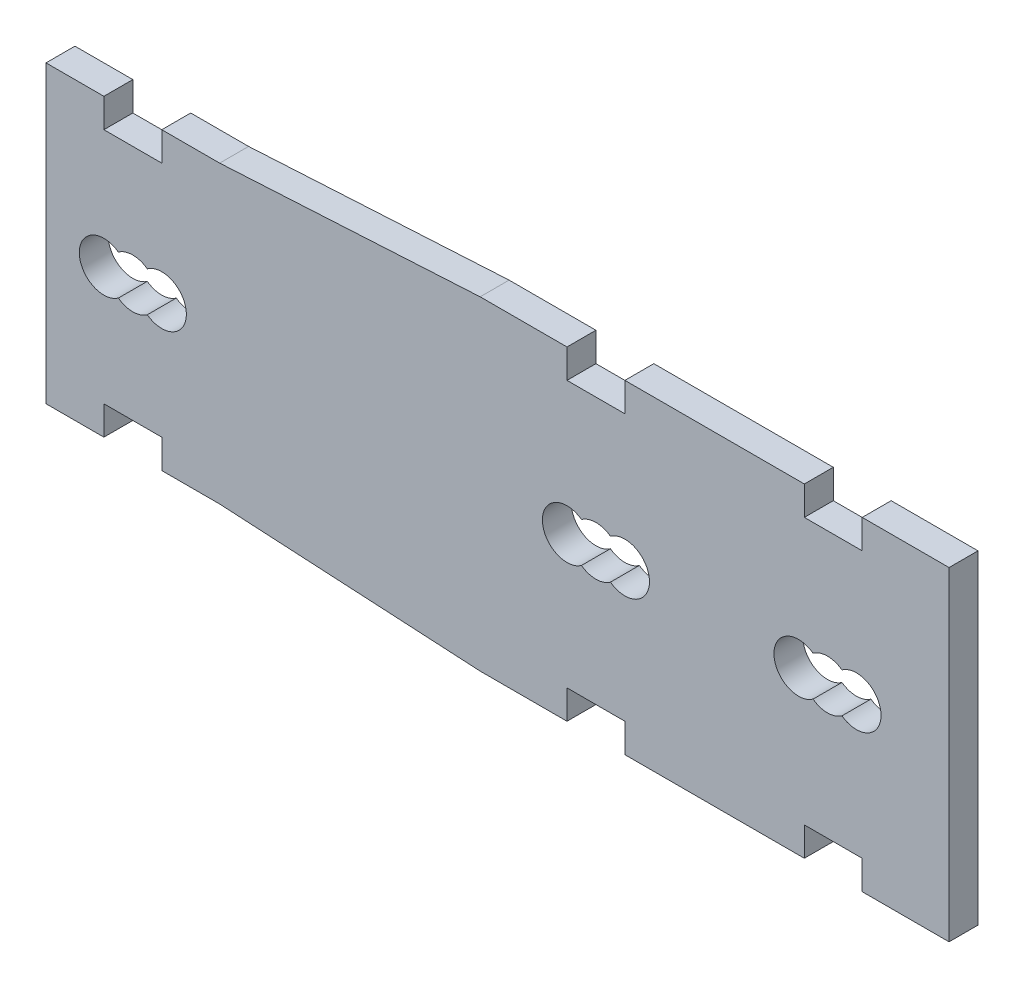
SolidWorks part; units mm, degrees
ref_plane "Front Plane" through (0, 0, 0) normal (1, 0, 0) x (0, 1, 0)
ref_plane "Top Plane" through (0, 0, 0) normal (0, 0, 1) x (0, 1, 0)
ref_plane "Right Plane" through (0, 0, 0) normal (0, 1, 0) x (-1, 0, 0)
sketch "Sketch1" plane through (0, 0, 0) normal (0, 0, 1) x (0, 1, 0)
  line L0 (0, 0) -> (0, 36284.5455) construction
  line L1 (-25.5, 50) -> (25.5, 50)
  line L2 (25.5, 50) -> (25.5, 40)
  line L3 (25.5, 40) -> (20.5, 40)
  line L4 (20.5, 40) -> (20.5, 30)
  line L5 (20.5, 30) -> (25.5, 30)
  line L6 (25.5, 30) -> (25.5, 20)
  line L7 (20.5, 35) -> (0, 35) construction
  line L8 (0, 35) -> (0, -25) construction
  line L9 (0, -25) -> (28, -25) construction
  line L10 (25.5, 20) -> (28, -25)
  line L11 (28, -25) -> (28, -40)
  line L12 (28, -25) -> (28, -40)
  line L13 (28, -50) -> (28, -86)
  line L14 (28, -106) -> (-28, -106)
  line L15 (28, -50) -> (28, -45) construction
  line L16 (28, -40) -> (23, -40)
  line L17 (28, -50) -> (23, -50)
  line L18 (23, -50) -> (23, -40)
  line L19 (28, -50) -> (28, -106)
  line L20 (28, -40) -> (28, -45) construction
  line L21 (28, -45) -> (28, -50) construction
  line L22 (28, -40) -> (28, -45) construction
  line L23 (28, -45) -> (28, -40) construction
  line L24 (28, -45) -> (28, -50) construction
  line L25 (28, -91) -> (28, -81)
  line L26 (28, -81) -> (23, -81)
  line L27 (23, -81) -> (23, -91)
  line L28 (23, -91) -> (28, -91)
  line L29 (28, -40) -> (28, -50)
  line L30 (-28, -50) -> (-28, -106)
  line L31 (-23, -91) -> (-28, -91)
  line L32 (-23, -81) -> (-23, -91)
  line L33 (-28, -81) -> (-23, -81)
  line L34 (-28, -50) -> (-28, -86)
  line L35 (-28, -50) -> (-23, -50)
  line L36 (-23, -50) -> (-23, -40)
  line L37 (-28, -40) -> (-23, -40)
  line L38 (-28, -25) -> (-28, -40)
  line L39 (-25.5, 20) -> (-28, -25)
  line L40 (-25.5, 30) -> (-25.5, 20)
  line L41 (-20.5, 30) -> (-25.5, 30)
  line L42 (-20.5, 40) -> (-20.5, 30)
  line L43 (-25.5, 40) -> (-20.5, 40)
  line L44 (-25.5, 50) -> (-25.5, 40)
  point P21 (28, -45)
  point P26 (28, -86)
  point P29 (0, -106)
  point P45 (0, 50)
  dimension "D1" = 25.5
  dimension "D2" = 10
  dimension "D3" = 10
  dimension "D4" = 5
  dimension "D5" = 50
  dimension "D6" = 28
  dimension "D7" = 60
  dimension "D8" = 20
  dimension "D9" = 41
  dimension "D10" = 20
  dimension "D11" = 10
  dimension "D12" = 5
  dimension "D13" = 10
  dimension "D14" = 5
extrude "Boss-Extrude1" add sketch "Sketch1" along normal mid plane 5 contours L1 L44 L43 L42 L41 L40 L39 L38 L37 L36 L35 L30 L33 L32 L31 L14 L19 L28 L27 L26 L13 L17 L18 L16 L11 L10 L6 L5 L4 L3 L2
sketch "Sketch2" plane through (0, 0, 2.5) normal (0, 0, 1) x (1, 0, 0)
  line L0 (-50, 0) -> (106, 0) construction
  line L1 (-50, -25.5) -> (-50, 25.5) construction
  line L2 (106, 28) -> (106, -28) construction
  line L3 (-50, 0) -> (-35, 0)
  line L4 (-35, 0) -> (45, 0)
  line L5 (45, 0) -> (85, 0)
  circle A0 centre (-35, 0) radius 4.25
  circle A1 centre (45, 0) radius 4.25
  circle A2 centre (85, 0) radius 4.25
  circle A3 centre (90, 0) radius 4.25
  circle A4 centre (50, 0) radius 4.25
  circle A5 centre (-30, 0) radius 4.25
  circle A6 centre (85, 0) radius 4.25
  circle A7 centre (45, 0) radius 4.25
  circle A8 centre (-35, 0) radius 4.25
  circle A9 centre (80, 0) radius 4.25
  circle A10 centre (40, 0) radius 4.25
  circle A11 centre (-40, 0) radius 4.25
  dimension "D4" = 8.5
  dimension "D1" = 15
  dimension "D2" = 80
  dimension "D3" = 40
extrude "Cut-Extrude1" cut sketch "Sketch2" against normal up to next contours A0 | A1 | A2 | A11 | A5 | A4 | A10 | A9 | A3
